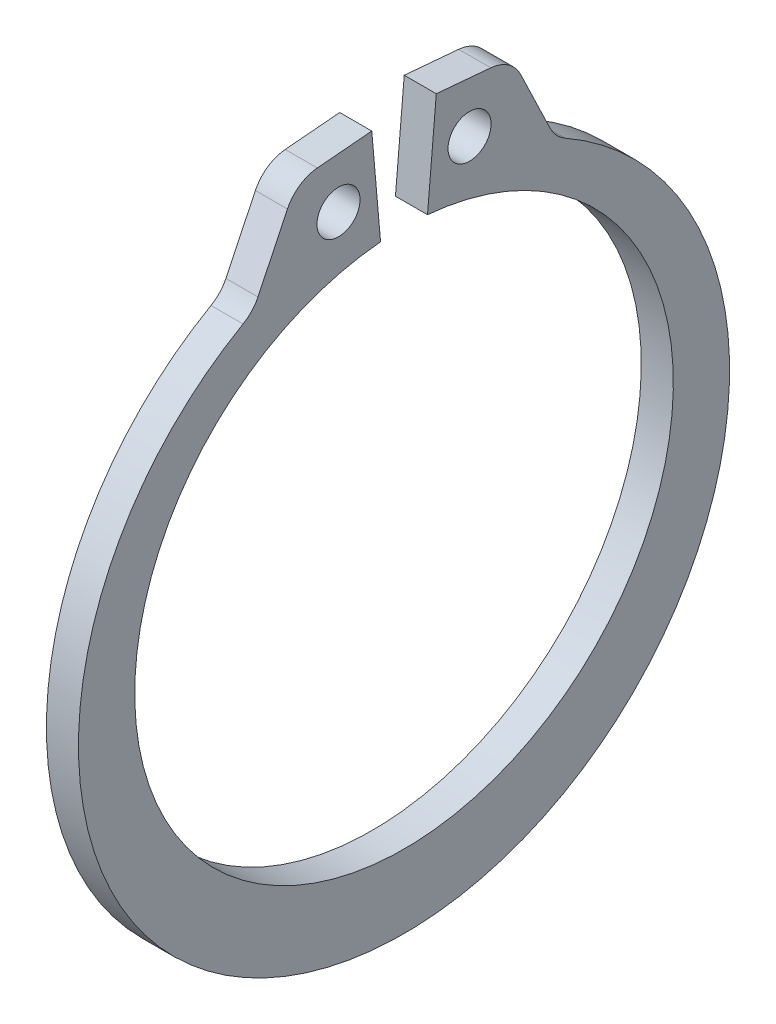
SolidWorks part; units mm, degrees
material "Cast Carbon Steel"
ref_plane "Front" through (0, 0, 0) normal (0, 0, 1) x (1, 0, 0)
ref_plane "Top" through (0, 0, 0) normal (0, 1, 0) x (1, 0, 0)
ref_plane "Right" through (0, 0, 0) normal (1, 0, 0) x (0, 0, -1)
sketch "Sketch1" plane through (0, 0, 0) normal (1, 0, 0) x (0, 0, -1)
  line L0 (0, 0) -> (0, 7.4676) construction
  line L1 (-0.6508, 7.4392) -> (-0.8944, 10.2226)
  line L2 (0.8944, 10.2226) -> (2.9819, 10.0399)
  line L3 (2.9819, 10.0399) -> (4.1917, 7.5214)
  line L4 (0.6508, 7.4392) -> (0.8944, 10.2226)
  line L5 (-0.8944, 10.2226) -> (-2.9819, 10.0399)
  line L6 (-2.9819, 10.0399) -> (-4.1917, 7.5214)
  line L7 (-4.1917, 7.5214) -> (-3.6353, 6.523) construction
  line L8 (4.1917, 7.5214) -> (3.6353, 6.523) construction
  line L9 (0, -7.4676) -> (0, -9.4996) construction
  line L10 (-2.9819, 10.0399) -> (-0.6508, 7.4392) construction
  line L11 (0, 7.4676) -> (0, 10.2616) construction
  line L12 (-7.4676, 0) -> (7.4676, 0) construction
  circle A0 centre (0, 0) radius 7.4676 construction
  arc A1 (-0.6508, 7.4392) -> (0.6508, 7.4392) centre (0, 0) ccw
  circle A3 centre (0, 0) radius 11.049 construction
  circle A4 centre (-1.8164, 8.7396) radius 0.5969
  circle A5 centre (1.8164, 8.7396) radius 0.5969
  arc A6 (-4.1917, 7.5214) -> (4.1917, 7.5214) centre (0, -0.4729) ccw
  point P0 (0, -9.4996)
  dimension "A" = 14.9352
  dimension "Hole" = 1.1938
  dimension "Smin" = 1.143
  dimension "H" = 2.794
  dimension "D2" = 2.0955
  dimension "Angle" = 5
extrude "Extrude1" add sketch "Sketch1" along normal mid plane 0.889
fillet "Fillet1" radius 1.016 4 edges at (0, 7.5214, 4.1917) (0, 7.5214, -4.1917) (0, 10.0399, 2.9819) (0, 10.0399, -2.9819)
sketch "Sketch2" plane through (0, 0, 0) normal (0, 0, 1) x (1, 0, 0)
  line L0 (-4.9403, 0) -> (12.8397, 0)
  line L1 (12.8397, 0) -> (12.8397, -7.9375)
  line L2 (-0.4953, -7.9375) -> (-4.4704, -7.9375)
  line L3 (12.8397, -7.9375) -> (0.4953, -7.9375)
  line L4 (0.4953, -7.9375) -> (0.4953, -7.4676)
  line L5 (0.4953, -7.4676) -> (-0.4953, -7.4676)
  line L6 (-0.4953, -7.4676) -> (-0.4953, -7.9375)
  line L7 (-0.4953, -7.9375) -> (-4.9403, -7.9375) construction
  line L8 (-4.9403, -7.9375) -> (-4.9403, 0) construction
  line L9 (12.8397, 0) -> (76.391, 0) construction
  line L10 (-4.4704, -7.9375) -> (-4.9403, -7.4676)
  line L11 (-4.9403, -7.4676) -> (-4.9403, 0)
  point P10 (0, -7.4676)
  dimension "D2" = 17.78
  dimension "D3" = 4.445
  dimension "D1" = 45
revolve "Revolve1" [suppressed] add sketch "Sketch2" angle 360 about L9
delete or keep bodies "Body-Delete1" [suppressed] type delete bodies bodies 122
equation "\"D2@Sketch2\" = \"D1@Extrude1\"*20"
equation "\"D3@Sketch2\" = \"D2@Sketch2\"/4"
equation "\"D2@Sketch1\" = \"H@Sketch1\"*.75"
